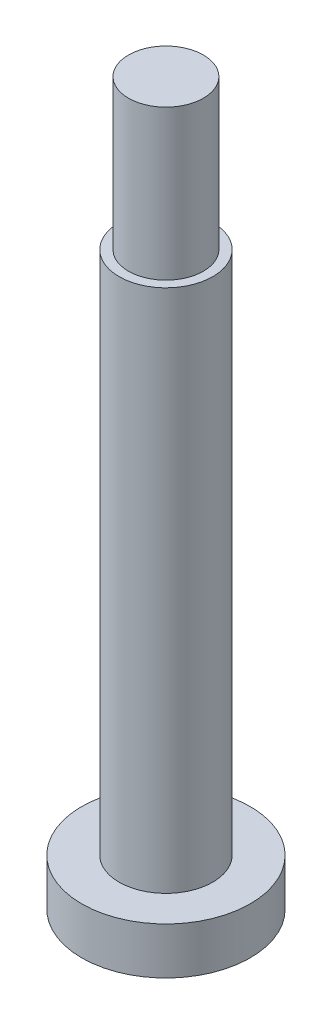
SolidWorks part; units mm, degrees
ref_plane "前视基准面" through (0, 0, 0) normal (0, 0, 1) x (1, 0, 0)
ref_plane "上视基准面" through (0, 0, 0) normal (0, 1, 0) x (1, 0, 0)
ref_plane "右视基准面" through (0, 0, 0) normal (1, 0, 0) x (0, 0, -1)
sketch "草图1" plane through (0, 0, 0) normal (0, 1, 0) x (1, 0, 0)
  circle A0 centre (0, 0) radius 4.5
  dimension "D1" = 9
extrude "凸台-拉伸1" add sketch "草图1" along normal blind 2.5
sketch "草图2" plane through (0, 2.5, 0) normal (0, 1, 0) x (1, 0, 0)
  circle A0 centre (0, 0) radius 2.5
  dimension "D1" = 5
extrude "凸台-拉伸2" add sketch "草图2" along normal blind 28
sketch "草图3" plane through (0, 30.5, 0) normal (0, 1, 0) x (1, 0, 0)
  circle A0 centre (0, 0) radius 2
  dimension "D1" = 4
extrude "凸台-拉伸3" add sketch "草图3" along normal blind 8
cosmetic thread "装饰螺纹线1" parameters "D1"=4, "D2"=3.242
